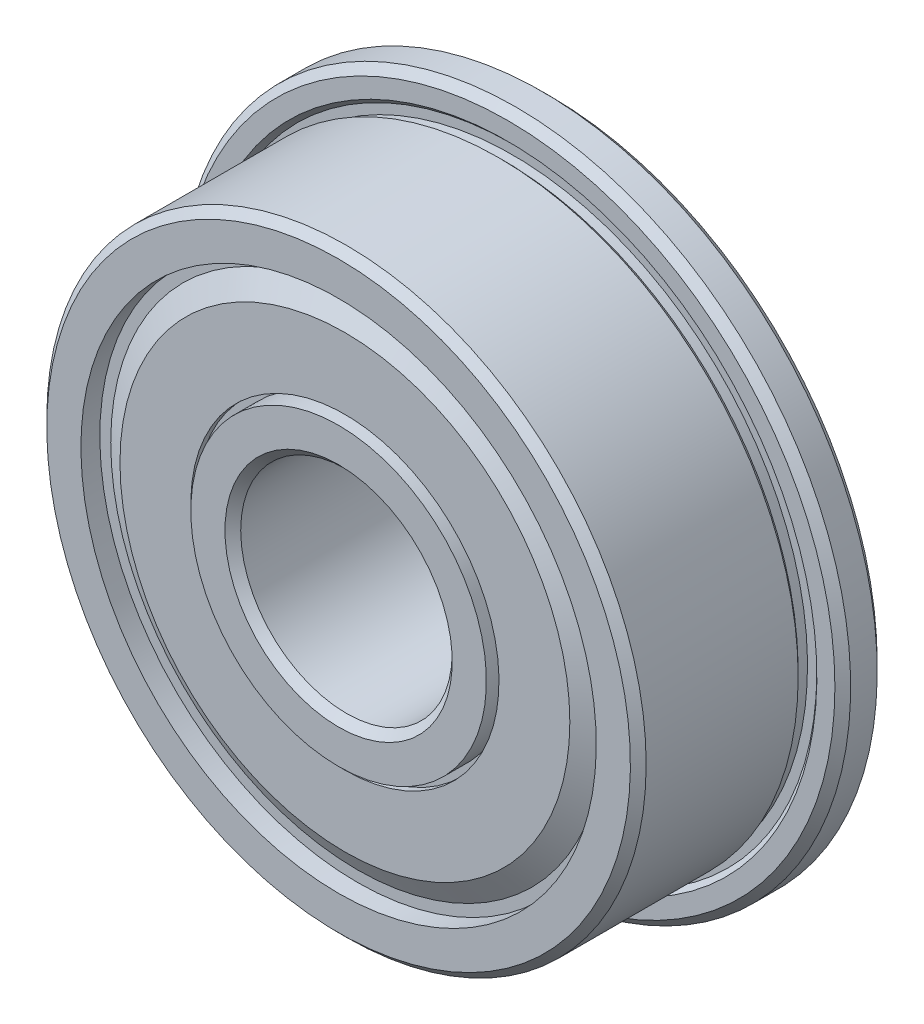
SolidWorks part; units mm, degrees
ref_plane "Front Plane" through (0, 0, 0) normal (0, 0, 1) x (1, 0, 0)
ref_plane "Top Plane" through (0, 0, 0) normal (0, 1, 0) x (1, 0, 0)
ref_plane "Right Plane" through (0, 0, 0) normal (1, 0, 0) x (0, 0, -1)
sketch "Sketch1" plane through (0, 0, 0) normal (1, 0, 0) x (0, 0, -1)
  line L0 (0, 8.5) -> (0, -8.5) construction
  line L1 (-3, 8.5) -> (3, 8.5) construction
  line L2 (0, 0) -> (3, 0) construction
  line L3 (3, 9.5) -> (3, -9.5) construction
  line L4 (3, -9.5) -> (1.8, -9.5) construction
  line L5 (3, 3) -> (0, 3) construction
  line L6 (3, 3) -> (3, -3) construction
  dimension "OD" = 17
  dimension "Width" = 6
  dimension "Flange Thickness" = 1.2
  dimension "ID" = 6
  dimension "Flange OD" = 19
sketch "Sketch2" plane through (0, 0, 0) normal (1, 0, 0) x (0, 0, -1)
  line L0 (3, 9.5) -> (1.8, 9.5)
  line L1 (1.8, 9.5) -> (1.8, 8.7652)
  line L2 (1.5348, 8.5) -> (-3, 8.5)
  line L3 (-3, 8.5) -> (-3, 6.7125)
  line L4 (-3, 6.7125) -> (-1.4615, 6.7125)
  line L5 (3, 9.5) -> (3, -9.5) construction
  line L6 (3, 6.7125) -> (3, 9.5)
  line L7 (3, 3) -> (-3, 3)
  line L8 (-3, 3) -> (-3, 4.7875)
  line L9 (-3, 4.7875) -> (-1.4615, 4.7875)
  line L10 (3, 4.7875) -> (3, 3)
  line L11 (0, 8.5) -> (0, 3) construction
  line L12 (-1.75, 5.75) -> (1.75, 5.75) construction
  line L13 (1.4615, 6.7125) -> (3, 6.7125)
  line L14 (1.4615, 4.7875) -> (3, 4.7875)
  line L15 (1.8, 8.7652) -> (1.9326, 8.6326)
  line L16 (1.9326, 8.6326) -> (1.9326, 8.3674)
  line L17 (1.9326, 8.3674) -> (1.6674, 8.3674)
  line L18 (1.6674, 8.3674) -> (1.5348, 8.5)
  line L19 (1.8, 8.5) -> (1.9326, 8.3674) construction
  line L20 (1.9326, 8.6326) -> (1.6674, 8.3674) construction
  line L21 (1.5348, 8.5) -> (1.8, 8.5) construction
  line L22 (1.8, 8.5) -> (1.8, 8.7652) construction
  line L23 (-3, 0) -> (3, 0) construction
  circle A0 centre (0, 5.75) radius 1.75 construction
  arc A1 (-1.4615, 6.7125) -> (1.4615, 6.7125) centre (0, 5.75) cw
  arc A2 (-1.4615, 4.7875) -> (1.4615, 4.7875) centre (0, 5.75) ccw
  dimension "Ball Dia." = 3.5
  dimension "D2" = 135
  dimension "D3" = 0.375
  dimension "Race Thikness" = 1.7875
  dimension "D4" = 1.925
revolve "Revolve1" add sketch "Sketch2" angle 360 about L2
fillet "Fillet1" radius 0.2234 3 edges at (0, -9.5, -3) (0, -9.5, -1.8) (0, -8.5, 3) profile chamfer
sketch "Sketch3" plane through (0, 0, 0) normal (0, 0, 1) x (1, 0, 0)
  line L0 (-3, 0) -> (3, 0) construction
  line L1 (-8.5, 0) -> (8.5, 0) construction
  point P5 (0, 0)
  dimension "ID2" = 6
  dimension "OD2" = 17
fillet "Fillet2" radius 0.2234 2 edges at (0, -3, -3) (0, -3, 3) profile chamfer
sketch "Sketch7" plane through (0, 0, 0) normal (0, 0, 1) x (1, 0, 0)
  line L0 (0, 7.5) -> (0, 4)
  line L1 (0, 9.5) -> (0, -9.5) construction
  line L2 (-2.3963, 7.5) -> (0, 0) construction
  line L3 (0, 0) -> (2.3963, 7.5) construction
  line L4 (2.3963, 7.5) -> (-2.3963, 7.5) construction
  circle A0 centre (0, 5.75) radius 1.75 construction
  circle A1 centre (0, 0) radius 7.5 construction
  circle A2 centre (0, 0) radius 4 construction
  arc A4 (0, 7.5) -> (0, 4) centre (0, 5.75) ccw
  dimension "D1" = 35.438
revolve "Revolve3" add sketch "Sketch7" angle 360 about L0
pattern_circular "CirPattern3" count 6 over 360 about axis through (0, 0, 0) along (0, 0, 1) of bodies 107
sketch "Sketch8" plane through (0, 0, 0) normal (1, 0, 0) x (0, 0, -1)
  line L1 (-3, 6.7125) -> (-2.285, 6.7125)
  line L2 (-3, 6.7125) -> (-3, 7.3083)
  line L3 (-3, 7.3083) -> (-2.285, 7.3083)
  line L4 (-2.285, 6.7125) -> (-2.285, 7.3083)
  line L5 (3, 6.7125) -> (2.285, 6.7125)
  line L6 (3, 6.7125) -> (3, 7.3083)
  line L7 (3, 7.3083) -> (2.285, 7.3083)
  line L8 (2.285, 6.7125) -> (2.285, 7.3083)
  line L9 (3, 4.7875) -> (2.285, 4.7875)
  line L10 (3, 4.7875) -> (3, 4.1917)
  line L11 (3, 4.1917) -> (2.285, 4.1917)
  line L12 (2.285, 4.7875) -> (2.285, 4.1917)
  line L13 (-3, 4.7875) -> (-2.285, 4.7875)
  line L14 (-3, 4.7875) -> (-3, 4.1917)
  line L15 (-3, 4.1917) -> (-2.285, 4.1917)
  line L16 (-2.285, 4.7875) -> (-2.285, 4.1917)
  dimension "D1" = 0.5958
  dimension "D2" = 0.715
revolve "Cut-Revolve1" cut sketch "Sketch8" angle 360 about L2
sketch "Sketch9" plane through (0, 0, 0) normal (1, 0, 0) x (0, 0, -1)
  line L0 (-2.285, 7.3083) -> (-2.285, 6.9512)
  line L1 (-2.285, 6.9512) -> (-2.6425, 6.332)
  line L2 (-2.6425, 6.332) -> (-2.6425, 4.3704)
  line L3 (2.6425, 4.3704) -> (2.6425, 4.1917) construction
  line L4 (2.285, 7.3083) -> (2.285, 6.9512)
  line L5 (2.285, 6.9512) -> (2.6425, 6.332)
  line L6 (2.6425, 6.332) -> (2.6425, 4.3704)
  line L7 (3, 4.1917) -> (2.285, 4.1917) construction
  line L8 (-2.4638, 7.3083) -> (-2.4638, 6.9991)
  line L9 (-2.4638, 6.9991) -> (-2.8213, 6.3799)
  line L10 (-2.8213, 6.3799) -> (-2.8213, 4.3704)
  line L11 (-2.285, 7.3083) -> (-2.4638, 7.3083)
  line L12 (-2.6425, 4.3704) -> (-2.8213, 4.3704)
  line L13 (2.4638, 7.3083) -> (2.4638, 6.9991)
  line L14 (2.4638, 6.9991) -> (2.8213, 6.3799)
  line L15 (2.8213, 6.3799) -> (2.8213, 4.3704)
  line L16 (2.285, 7.3083) -> (2.4638, 7.3083)
  line L17 (2.6425, 4.3704) -> (2.8213, 4.3704)
  line L18 (-2.285, 6.9512) -> (-2.285, 2.5308) construction
  line L19 (2.285, 6.9512) -> (2.285, 7.3083) construction
  line L20 (-2.285, 4.1917) -> (-3, 4.1917) construction
  line L22 (-2.6425, 4.3704) -> (-2.6425, 4.1917) construction
  dimension "D2" = 150
  dimension "D1" = 150
  dimension "D5" = 0.715
  dimension "D3" = 0.1787
  dimension "D4" = 0.1787
  dimension "D6" = 0.3571
revolve "Revolve4" add sketch "Sketch9" angle 360 about L2
equation "\"D1@Fillet1\"=\"Race Thikness@Sketch2\"/8"
equation "\"ID2@Sketch3\" = \"ID@Sketch1\""
equation "\"OD2@Sketch3\" = \"OD@Sketch1\""
equation "\"D1@Fillet2\"=\"Race Thikness@Sketch2\"/8"
equation "\"D1@CirPattern3\"=360/\"D1@Sketch7\"-4"
equation "\"D1@Sketch8\"=\"Race Thikness@Sketch2\"/3"
equation "\"D2@Sketch8\"=\"Race Thikness@Sketch2\"/2.5"
equation "\"D3@Sketch9\"=\"D5@Sketch9\"/4"
equation "\"D4@Sketch9\"=\"D5@Sketch9\"/4"
equation "\"D1@Sketch9\"=\"D2@Sketch9\""
equation "\"Ball Dia.@Sketch2\" = \"D1@Sketch2\"*.5"
equation "\"D4@Sketch2\"=((\"OD@Sketch1\"-\"ID@Sketch1\")/2)*.35"
